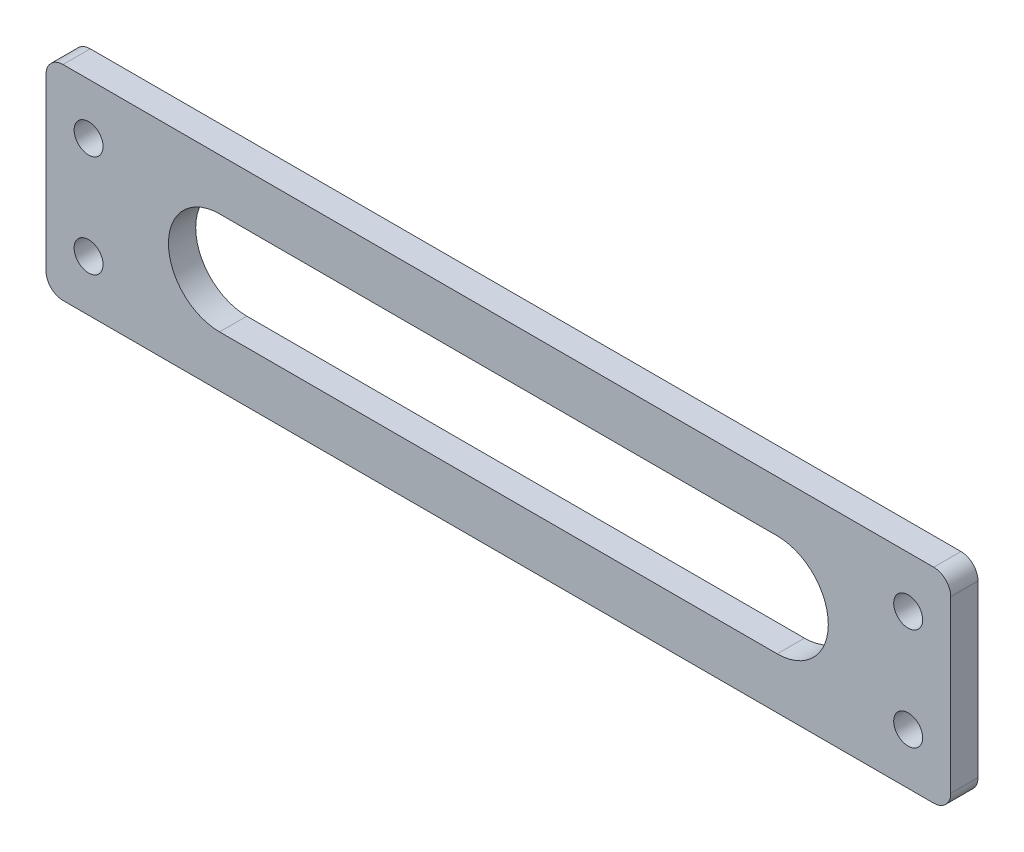
SolidWorks part; units mm, degrees
ref_plane "前视基准面" through (0, 0, 0) normal (0, 0, 1) x (1, 0, 0)
ref_plane "上视基准面" through (0, 0, 0) normal (0, 1, 0) x (1, 0, 0)
ref_plane "右视基准面" through (0, 0, 0) normal (1, 0, 0) x (0, 0, -1)
sketch "草图1" plane through (0, 0, 0) normal (0, 0, 1) x (1, 0, 0)
  line L0 (5, 0) -> (5, -12)
  line L1 (0, 0) -> (53.12, 0)
  line L2 (0, 0) -> (0, -12)
  line L3 (0, -12) -> (53.12, -12)
  line L4 (53.12, 0) -> (53.12, -12)
  line L5 (0, -6) -> (9.9072, -6) construction
  line L6 (0, 0) -> (5, -6) construction
  line L7 (5, -6) -> (0, -12) construction
  line L8 (26.56, 0) -> (26.56, -5.0482) construction
  circle A0 centre (2.5, -3) radius 0.85
  circle A1 centre (2.5, -9) radius 0.85
  circle A2 centre (50.62, -9) radius 0.85
  circle A3 centre (50.62, -3) radius 0.85
  dimension "D4" = 1.7
  dimension "D5" = 1.7
  dimension "D1" = 53.12
  dimension "D2" = 12
  dimension "D3" = 5
extrude "凸台-拉伸1" add sketch "草图1" along normal blind 1.6 contours L4 L1 L0 L3 A2 A3 | L2 L3 L0 L1 A1 A0
sketch "草图2" plane through (0, 0, 0) normal (0, 0, -1) x (-1, 0, 0)
  line L0 (-53.12, -6) -> (0, -6) construction
  line L1 (-53.12, 0) -> (-53.12, -12) construction
  line L2 (0, 0) -> (0, -12) construction
  line L3 (-42.9308, -6) -> (-10.1892, -6) construction
  line L4 (-42.9308, -3) -> (-10.1892, -3)
  line L5 (-42.9308, -9) -> (-10.1892, -9)
  arc A0 (-42.9308, -3) -> (-42.9308, -9) centre (-42.9308, -6) ccw
  arc A1 (-10.1892, -9) -> (-10.1892, -3) centre (-10.1892, -6) ccw
  point P8 (-26.56, -6)
  dimension "D1" = 3
extrude "切除-拉伸1" cut sketch "草图2" against normal blind 1.6
fillet "圆角1" radius 1 4 edges at (0, 0, 0.8) (0, -12, 0.8) (53.12, -12, 0.8) (53.12, 0, 0.8)
